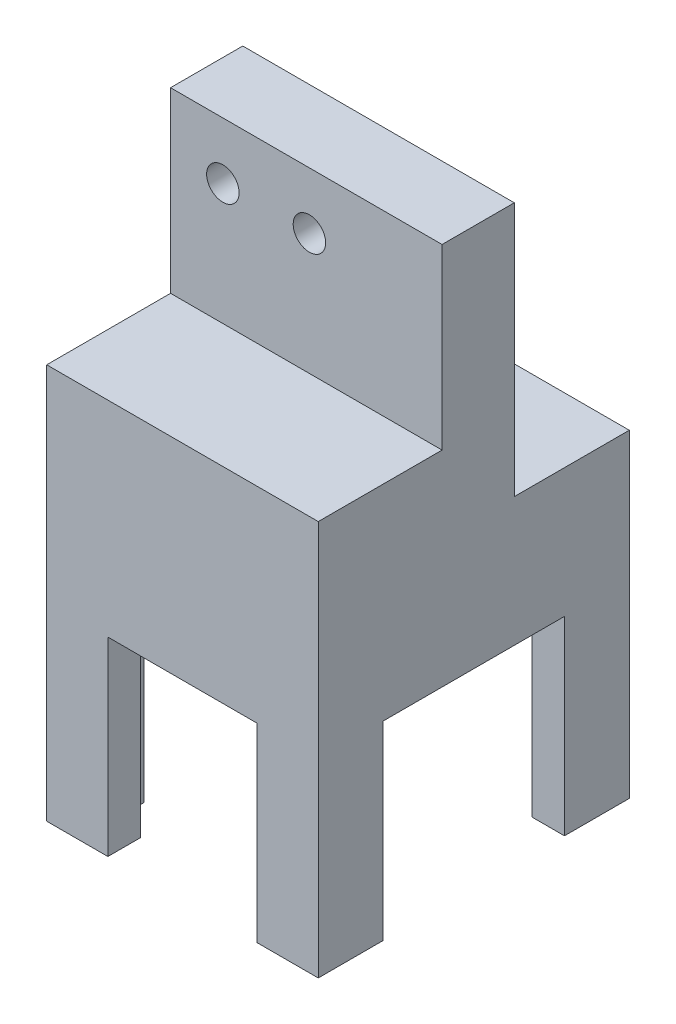
SolidWorks part; units mm, degrees
ref_plane "Front Plane" through (0, 0, 0) normal (0, 0, 1) x (1, 0, 0)
ref_plane "Top Plane" through (0, 0, 0) normal (0, 1, 0) x (1, 0, 0)
ref_plane "Right Plane" through (0, 0, 0) normal (1, 0, 0) x (0, 0, -1)
sketch "Sketch4" plane through (0, 0, 0) normal (0, 1, 0) x (1, 0, 0)
  line L1 (-12.55, 14.375) -> (12.55, 14.375)
  line L2 (-12.55, 14.375) -> (-12.55, -14.375)
  line L3 (-12.55, -14.375) -> (12.55, -14.375)
  line L4 (12.55, 14.375) -> (12.55, -14.375)
  line L5 (-12.55, 14.375) -> (12.55, -14.375) construction
  line L6 (-12.55, -14.375) -> (12.55, 14.375) construction
  point P0 (0, 0)
  dimension "D1" = 28.75
  dimension "D2" = 25.1
extrude "Boss-Extrude2" add sketch "Sketch4" along normal blind 53
sketch "Sketch5" plane through (0, 0, 0) normal (0, -1, 0) x (-1, 0, 0)
  line L0 (-12.55, -14.375) -> (-12.55, 14.375) construction
  line L1 (9.55, -11.375) -> (-9.55, -11.375)
  line L2 (9.55, -11.375) -> (9.55, 11.375)
  line L3 (9.55, 11.375) -> (-9.55, 11.375)
  line L4 (-9.55, -11.375) -> (-9.55, 11.375)
  line L5 (9.55, -11.375) -> (-9.55, 11.375) construction
  line L6 (9.55, 11.375) -> (-9.55, -11.375) construction
  line L7 (-12.55, 14.375) -> (12.55, 14.375) construction
  point P0 (0, 0)
  dimension "D1" = 22.75
  dimension "D2" = 19.1
  dimension "D3" = 3
  dimension "D4" = 3
extrude "Cut-Extrude1" cut sketch "Sketch5" against normal blind 21.67
fillet "Fillet1" radius 4.1 2 edges at (0, 21.67, -11.375) (0, 21.67, 11.375)
sketch "Sketch6" plane through (0, 21.67, 0) normal (0, -1, 0) x (-1, 0, 0)
  line L1 (1.44, 2.55) -> (-1.44, 2.55)
  line L2 (1.44, 2.55) -> (1.44, -2.55)
  line L3 (1.44, -2.55) -> (-1.44, -2.55)
  line L4 (-1.44, 2.55) -> (-1.44, -2.55)
  line L5 (1.44, 2.55) -> (-1.44, -2.55) construction
  line L6 (1.44, -2.55) -> (-1.44, 2.55) construction
  point P0 (0, 0)
  dimension "D1" = 2.88
  dimension "D2" = 5.1
extrude "Cut-Extrude2" cut sketch "Sketch6" against normal blind 4.67
sketch "Sketch7" plane through (12.55, 0, 0) normal (1, 0, 0) x (0, 0, -1)
  line L0 (-14.375, 53) -> (-14.375, 0) construction
  line L1 (-8.3848, -17.57) -> (8.3848, -17.57)
  line L2 (-8.3848, -17.57) -> (-8.3848, 17.57)
  line L3 (-8.3848, 17.57) -> (8.3848, 17.57)
  line L4 (8.3848, -17.57) -> (8.3848, 17.57)
  line L5 (-8.3848, -17.57) -> (8.3848, 17.57) construction
  line L6 (-8.3848, 17.57) -> (8.3848, -17.57) construction
  point P0 (0, 0)
  dimension "D1" = 35.14
  dimension "D2" = 5.9902
extrude "Cut-Extrude3" cut sketch "Sketch7" against normal blind 40
sketch "Sketch8" plane through (0, 0, -14.375) normal (0, 0, -1) x (-1, 0, 0)
  line L0 (12.55, 53) -> (12.55, 0) construction
  line L1 (-6.8992, -17.57) -> (6.8992, -17.57)
  line L2 (-6.8992, -17.57) -> (-6.8992, 17.57)
  line L3 (-6.8992, 17.57) -> (6.8992, 17.57)
  line L4 (6.8992, -17.57) -> (6.8992, 17.57)
  line L5 (-6.8992, -17.57) -> (6.8992, 17.57) construction
  line L6 (-6.8992, 17.57) -> (6.8992, -17.57) construction
  line L7 (-12.55, 53) -> (-12.55, 0) construction
  point P0 (0, 0)
  dimension "D1" = 35.14
  dimension "D2" = 5.6508
  dimension "D3" = 5.6508
extrude "Cut-Extrude4" cut sketch "Sketch8" against normal blind 40
sketch "Sketch9" plane through (-12.55, 0, 0) normal (-1, 0, 0) x (0, 0, 1)
  line L0 (-14.375, 53) -> (14.375, 53) construction
  line L1 (5.875, 53) -> (14.375, 53)
  line L2 (5.875, 53) -> (5.875, 36.54)
  line L3 (5.875, 36.54) -> (14.375, 36.54)
  line L4 (14.375, 53) -> (14.375, 36.54)
  line L5 (14.375, 53) -> (14.375, 0) construction
  dimension "D1" = 16.46
  dimension "D2" = 8.5
extrude "Cut-Extrude5" cut sketch "Sketch9" against normal blind 40
sketch "Sketch10" plane through (-12.55, 0, 0) normal (-1, 0, 0) x (0, 0, 1)
  line L1 (-14.375, 53) -> (-3.7457, 53)
  line L2 (-14.375, 53) -> (-14.375, 29.4765)
  line L3 (-14.375, 29.4765) -> (-3.7457, 29.4765)
  line L4 (-3.7457, 53) -> (-3.7457, 29.4765)
extrude "Cut-Extrude6" cut sketch "Sketch10" against normal blind 40
sketch "Sketch11" plane through (0, 53, 0) normal (0, 1, 0) x (1, 0, 0)
  line L0 (12.55, -5.875) -> (12.55, 3.7457) construction
  line L1 (-12.55, -5.875) -> (12.55, -5.875)
  line L2 (-12.55, -5.875) -> (-12.55, -2.9302)
  line L3 (-12.55, -2.9302) -> (12.55, -2.9302)
  line L4 (12.55, -5.875) -> (12.55, -2.9302)
  dimension "D1" = 2.9448
extrude "Cut-Extrude7" cut sketch "Sketch11" against normal blind 16.46
sketch "Sketch13" plane through (0, 0, -3.7457) normal (0, 0, -1) x (-1, 0, 0)
  circle A0 centre (7.7132, 47.7476) radius 1.5
  dimension "D1" = 3
sketch "Sketch14" plane through (0, 0, -3.7457) normal (0, 0, -1) x (-1, 0, 0)
  circle A0 centre (-0.2868, 47.7476) radius 1.5
  circle A1 centre (7.7132, 47.7476) radius 1.5 construction
  dimension "D1" = 3
  dimension "D2" = 8
extrude "Cut-Extrude10" cut sketch "Sketch14" against normal blind 23.1
extrude "Cut-Extrude11" cut sketch "Sketch13" against normal blind 23.1 contours A0
